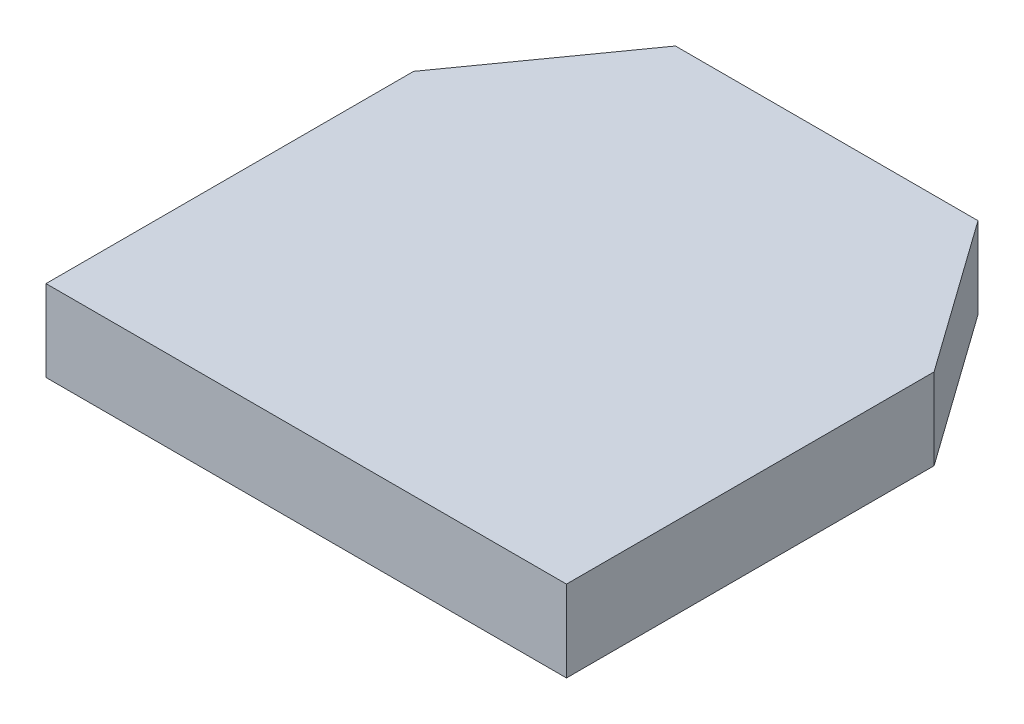
SolidWorks part; units mm, degrees
ref_plane "Front Plane" through (0, 0, 0) normal (0, 0, 1) x (1, 0, 0)
ref_plane "Top Plane" through (0, 0, 0) normal (0, 1, 0) x (1, 0, 0)
ref_plane "Right Plane" through (0, 0, 0) normal (1, 0, 0) x (0, 0, -1)
sketch "Sketch1" plane through (0, 0, 0) normal (0, 1, 0) x (1, 0, 0)
  line L0 (0, 28.702) -> (8.509, 40.64)
  line L1 (0, 0) -> (40.64, 0)
  line L2 (0, 0) -> (0, 28.702)
  line L3 (8.509, 40.64) -> (32.131, 40.64)
  line L4 (40.64, 0) -> (40.64, 28.702)
  line L5 (40.64, 28.702) -> (32.131, 40.64)
  point P1 (40.64, 40.64)
  point P2 (0, 40.64)
  dimension "D1" = 40.64
  dimension "D2" = 40.64
  dimension "D3" = 11.938
  dimension "D4" = 8.509
  dimension "D5" = 11.938
  dimension "D6" = 8.509
extrude "Boss-Extrude1" add sketch "Sketch1" along normal blind 6.35
ref_plane "Plane1" through (20.32, 0, 0) normal (1, 0, 0) x (0, 0, -1)
